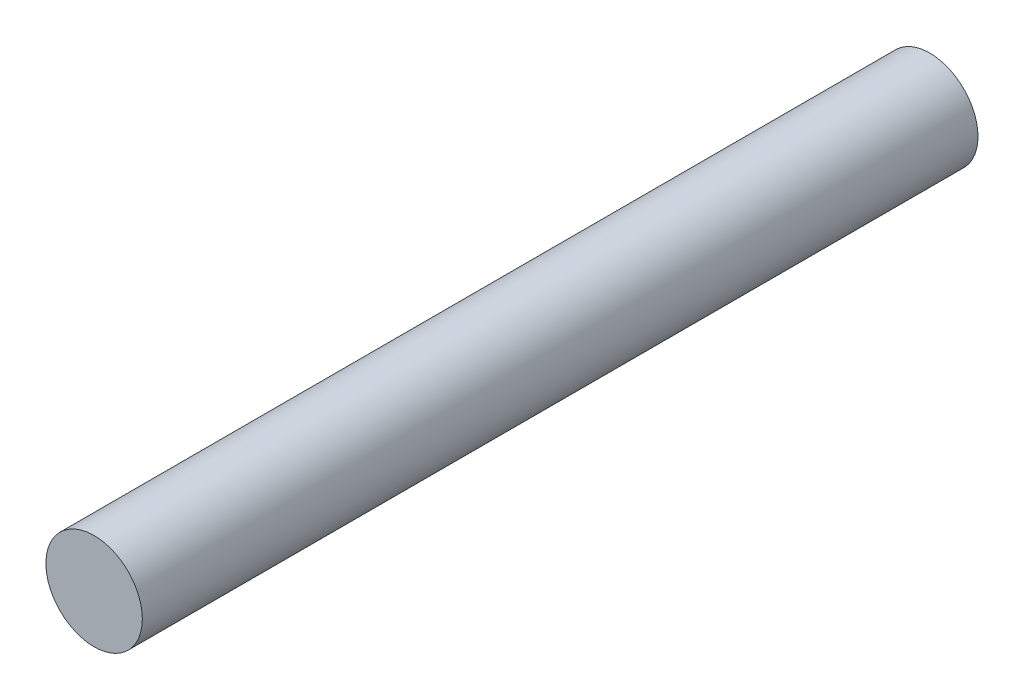
SolidWorks part; units mm, degrees
ref_plane "Front Plane" through (0, 0, 0) normal (0, 0, 1) x (1, 0, 0)
ref_plane "Top Plane" through (0, 0, 0) normal (0, 1, 0) x (1, 0, 0)
ref_plane "Right Plane" through (0, 0, 0) normal (1, 0, 0) x (0, 0, -1)
sketch "Sketch1" plane through (0, 0, 0) normal (0, 0, 1) x (1, 0, 0)
  circle A0 centre (0, 0) radius 7.5
  dimension "D1" = 15
extrude "Boss-Extrude1" add sketch "Sketch1" along normal blind 130
